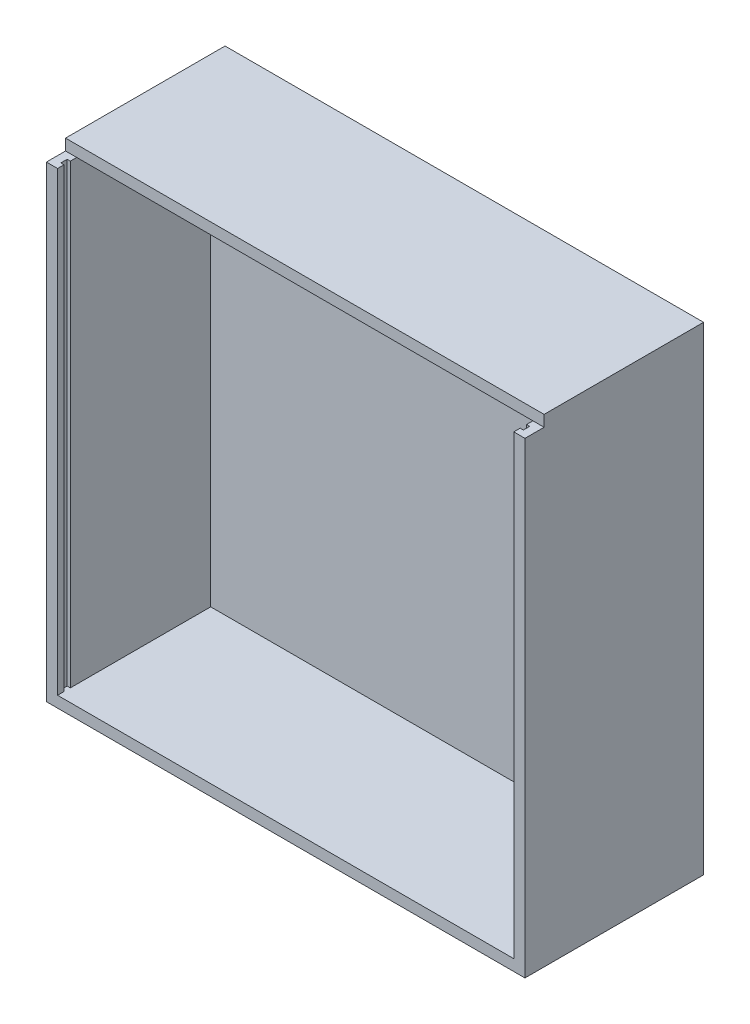
SolidWorks part; units mm, degrees
ref_plane "Front Plane" through (0, 0, 0) normal (0, 0, 1) x (1, 0, 0)
ref_plane "Top Plane" through (0, 0, 0) normal (0, 1, 0) x (1, 0, 0)
ref_plane "Right Plane" through (0, 0, 0) normal (1, 0, 0) x (0, 0, -1)
sketch "Sketch1" plane through (0, 0, 0) normal (0, 0, 1) x (1, 0, 0)
  line L1 (-75, -75) -> (75, -75)
  line L2 (-75, -75) -> (-75, 75)
  line L3 (-75, 75) -> (75, 75)
  line L4 (75, -75) -> (75, 75)
  line L5 (0, 75) -> (0, -75) construction
  line L6 (-75, 0) -> (75, 0) construction
  point P0 (0, 0)
  dimension "D1" = 150
extrude "Boss-Extrude1" add sketch "Sketch1" along normal blind 8
sketch "Sketch4" plane through (0, 0, 8) normal (0, 0, 1) x (1, 0, 0)
  line L0 (-75, 75) -> (75, 75)
  line L1 (75, 75) -> (75, -75)
  line L2 (75, -75) -> (-75, -75)
  line L3 (-75, -75) -> (-75, 75)
  line L4 (-71.5, 71.5) -> (-71.5, -71.5)
  line L7 (-71.5, -71.5) -> (71.5, -71.5)
  line L8 (71.5, -71.5) -> (71.5, 71.5)
  line L9 (71.5, 71.5) -> (-71.5, 71.5)
  dimension "D3" = 143
  dimension "D4" = 143
extrude "Boss-Extrude2" add sketch "Sketch4" along normal blind 42
sketch "Sketch5" plane through (0, 0, 50) normal (0, 0, 1) x (1, 0, 0)
  line L5 (71.5, 71.5) -> (71.5, -71.5)
  line L6 (71.5, -71.5) -> (-71.5, -71.5)
  line L7 (-71.5, -71.5) -> (-71.5, 71.5)
extrude "Extrude-Thin1" add sketch "Sketch5" along normal blind 6 thin thin type one direction reverse wall 3.5
sketch "Sketch6" plane through (0, 71.5, 0) normal (0, 1, 0) x (1, 0, 0)
  line L0 (71.5, -56) -> (71.5, -50) construction
  line L5 (72.5, -52) -> (70.5, -52)
  line L6 (72.5, -52) -> (72.5, -54)
  line L7 (72.5, -54) -> (70.5, -54)
  line L8 (70.5, -52) -> (70.5, -54)
  line L9 (71.5, -54) -> (71.5, -52) construction
  line L10 (72.5, -53) -> (70.5, -53) construction
  point P0 (71.5, -53)
  dimension "D1" = 2
extrude "Cut-Extrude1" cut sketch "Sketch6" against normal up to surface (143 mm away) up to face at (0, -71.5, 32)
mirror "Mirror1" about plane through (0, 0, 0) normal (1, 0, 0) of "Cut-Extrude1"
